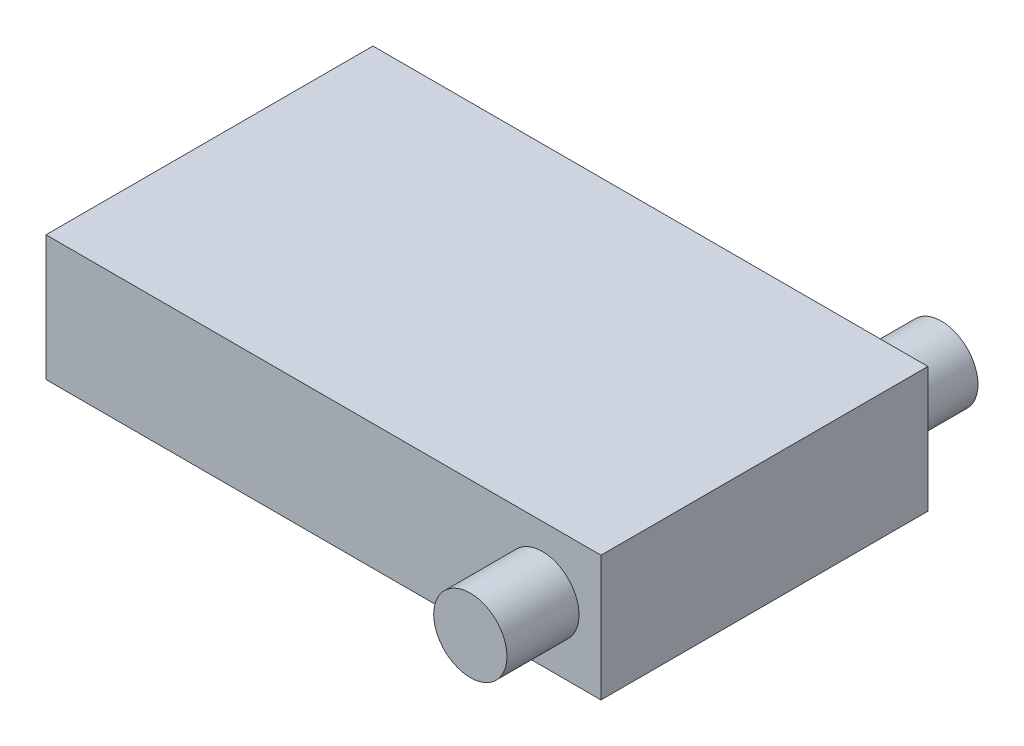
SolidWorks part; units mm, degrees
ref_plane "Front Plane" through (0, 0, 0) normal (0, 0, 1) x (1, 0, 0)
ref_plane "Top Plane" through (0, 0, 0) normal (0, 1, 0) x (1, 0, 0)
ref_plane "Right Plane" through (0, 0, 0) normal (1, 0, 0) x (0, 0, -1)
sketch "Sketch1" plane through (0, 0, 0) normal (0, 1, 0) x (1, 0, 0)
  line L0 (-55, 0) -> (55, 0) construction
  line L1 (-23.68, 13.95) -> (23.68, 13.95)
  line L2 (-23.68, 13.95) -> (-23.68, -13.95)
  line L3 (-23.68, -13.95) -> (23.68, -13.95)
  line L4 (23.68, 13.95) -> (23.68, -13.95)
  line L6 (0, -55) -> (0, 55) construction
  point P4 (23.68, 0)
  point P8 (0, 13.95)
  dimension "D1" = 47.36
  dimension "D2" = 27.9
extrude "Boss-Extrude1" add sketch "Sketch1" along normal mid plane 10.7
sketch "Sketch2" plane through (9.73, 0, -13.95) normal (0, 0, 1) x (1, 0, 0)
  line L0 (13.95, 5.35) -> (13.95, -5.35) construction
  line L1 (5.615, 0) -> (-25.075, 0) construction
  circle A0 centre (8.95, 0) radius 3.125
  dimension "D1" = 6.25
  dimension "D2" = 5
extrude "Boss-Extrude2" add sketch "Sketch2" against normal blind 6.15
mirror "Lustro1" about plane through (0, 0, 0) normal (0, 0, 1) of "Boss-Extrude2"
sketch "Sketch3" plane through (-23.68, 0, 0) normal (-1, 0, 0) x (0, 0, 1)
  line L0 (-13.95, -5.35) -> (13.95, -5.35) construction
  line L1 (-10.25, 0.95) -> (0.95, 0.95)
  line L2 (-10.25, 0.95) -> (-10.25, -4.05)
  line L3 (-10.25, -4.05) -> (0.95, -4.05)
  line L4 (0.95, 0.95) -> (0.95, -4.05)
  line L5 (-13.95, 5.35) -> (-13.95, -5.35) construction
  dimension "D1" = 11.2
  dimension "D2" = 1.3
  dimension "D3" = 3.7
  dimension "D4" = 5
extrude "Cut-Extrude1" cut sketch "Sketch3" against normal blind 1
sketch "Sketch5" plane through (-23.68, 0, 0) normal (-1, 0, 0) x (0, 0, 1)
  line L1 (0.95, 0.95) -> (9.85, 0.95)
  line L2 (0.95, 0.95) -> (0.95, -2.25)
  line L3 (0.95, -2.25) -> (9.85, -2.25)
  line L4 (9.85, 0.95) -> (9.85, -2.25)
  dimension "D1" = 3.2
  dimension "D2" = 8.9
extrude "Cut-Extrude2" cut sketch "Sketch5" against normal blind 1
